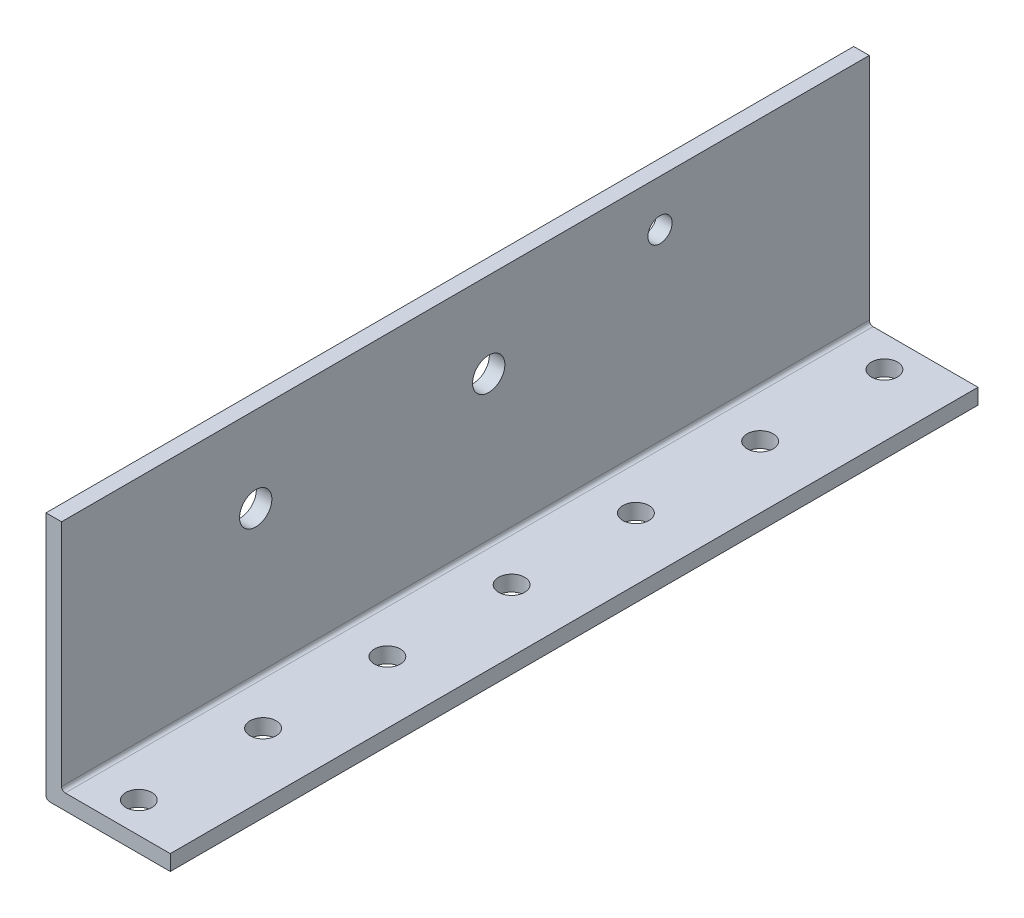
SolidWorks part; units mm, degrees
ref_plane "Front Plane" through (0, 0, 0) normal (0, 0, 1) x (1, 0, 0)
ref_plane "Top Plane" through (0, 0, 0) normal (0, 1, 0) x (1, 0, 0)
ref_plane "Right Plane" through (0, 0, 0) normal (1, 0, 0) x (0, 0, -1)
sketch "Sketch1" plane through (0, 0, 0) normal (0, 0, 1) x (1, 0, 0)
  line L0 (3.175, 50.8) -> (3.175, 3.937)
  line L1 (0.762, 0) -> (25.4, 0)
  line L2 (0, 0.762) -> (0, 50.8)
  line L3 (0, 50.8) -> (3.175, 50.8)
  line L4 (25.4, 0) -> (25.4, 3.175)
  line L5 (3.937, 3.175) -> (25.4, 3.175)
  arc A0 (0, 0.762) -> (0.762, 0) centre (0.762, 0.762) ccw
  arc A1 (3.175, 3.937) -> (3.937, 3.175) centre (3.937, 3.937) ccw
  point P10 (0, 0)
  dimension "D5" = 0.762
  dimension "D6" = 0.762
  dimension "D1" = 25.4
  dimension "D2" = 50.8
  dimension "D3" = 3.175
  dimension "D4" = 3.175
extrude "Boss-Extrude1" add sketch "Sketch1" along normal blind 165.1
sketch "Sketch3" plane through (0, 0, 0) normal (0, -1, 0) x (1, 0, 0)
  line L0 (0.762, 0) -> (25.4, 0) construction
  line L2 (25.4, 165.1) -> (25.4, 0) construction
  circle A0 centre (12.7, 6.4287) radius 2.667
  circle A1 centre (12.7, 31.8287) radius 2.667
  circle A2 centre (12.7, 57.2287) radius 2.667
  circle A3 centre (12.7, 82.6287) radius 2.667
  circle A4 centre (12.7, 108.0287) radius 2.667
  circle A5 centre (12.7, 133.4287) radius 2.667
  circle A6 centre (12.7, 158.8287) radius 2.667
  dimension "D2" = 5.334
  dimension "D1" = 6.4287
  dimension "D3" = 12.7
  dimension "D4" = 7
extrude "Cut-Extrude2" cut sketch "Sketch3" against normal up to surface (3.175 mm away) up to face at (14.6685, 3.175, 82.55)
sketch "Sketch4" plane through (3.175, 0, 0) normal (1, 0, 0) x (0, 0, -1)
  line L0 (-165.1, 50.8) -> (-165.1, 0.762) construction
  line L1 (-165.1, 0.762) -> (0, 0.762) construction
  circle A2 centre (-77.7875, 33.3375) radius 3.302
  circle A3 centre (-125.4125, 33.3375) radius 3.302
  dimension "D4" = 6.604
  dimension "D1" = 47.625
  dimension "D2" = 39.6875
  dimension "D3" = 32.5755
extrude "Cut-Extrude3" cut sketch "Sketch4" against normal up to surface (3.175 mm away) up to face at (0, 25.781, 82.55)
sketch "Sketch5" plane through (6.35, 0, 0) normal (1, 0, 0) x (0, 0, -1)
  line L0 (-165.1, 50.8) -> (0, 50.8) construction
  line L1 (-165.1, 50.8) -> (-165.1, 0.762) construction
  circle A0 centre (-42.7731, 41.3471) radius 2.4765
  point P2 (0, 0)
  dimension "D1" = 4.953
  dimension "D2" = 9.4529
  dimension "D3" = 122.3269
extrude "Cut-Extrude4" cut sketch "Sketch5" against normal up to surface (6.35 mm away) up to face at (0, 33.3375, 122.1105)
